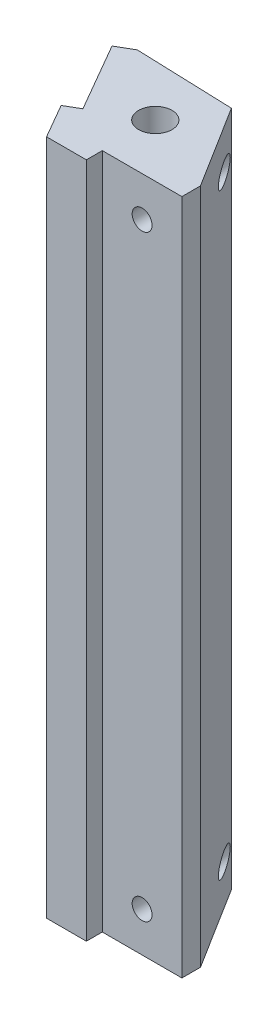
SolidWorks part; units mm, degrees
material "6061-T6 (SS)"
ref_plane "Front Plane" through (0, 0, 0) normal (0, 0, 1) x (1, 0, 0)
ref_plane "Top Plane" through (0, 0, 0) normal (0, 1, 0) x (1, 0, 0)
ref_plane "Right Plane" through (0, 0, 0) normal (1, 0, 0) x (0, 0, -1)
sketch "Sketch1" plane through (0, 0, 0) normal (0, 1, 0) x (1, 0, 0)
  line L0 (0, 0) -> (15, 0)
  line L1 (0, 0) -> (-7.5, 12.9904)
  line L2 (15, 0) -> (15, 4.3301)
  line L3 (0, 0) -> (2.5, 4.3301) construction
  line L6 (-3.75, 15.1554) -> (-7.5, 12.9904)
  line L7 (-3.75, 15.1554) -> (8.5, 14.7224)
  line L8 (8.5, 14.7224) -> (15, 4.3301)
  line L9 (2.5, 4.3301) -> (8.5, 14.7224) construction
  line L10 (-3.75, 15.1554) -> (2.5, 4.3301) construction
  line L11 (2.5, 4.3301) -> (15, 4.3301) construction
  dimension "D4" = 12
  dimension "D1" = 5
  dimension "D2" = 15
  dimension "D3" = 240
extrude "Boss-Extrude1" add sketch "Sketch1" along normal blind 85
sketch "Sketch3" plane through (0, 85, 0) normal (0, 1, 0) x (1, 0, 0)
  line L0 (-7.5, 12.9904) -> (-5.7679, 13.9904)
  line L1 (-3.75, 15.1554) -> (-7.5, 12.9904) construction
  line L2 (-5.7679, 13.9904) -> (-0.7679, 5.3301)
  line L3 (-0.7679, 5.3301) -> (-2.5, 4.3301)
  line L4 (-7.5, 12.9904) -> (0, 0) construction
  line L5 (-2.5, 4.3301) -> (-7.5, 12.9904)
  line L6 (15, 0) -> (15, 2)
  line L7 (15, 0) -> (15, 4.3301) construction
  line L8 (15, 2) -> (5, 2)
  line L9 (5, 2) -> (5, 0)
  line L11 (5, 0) -> (15, 0)
  line L12 (0, 0) -> (15, 0) construction
  dimension "D1" = 2
  dimension "D2" = 5
extrude "Cut-Extrude1" cut sketch "Sketch3" against normal through all
sketch "Sketch4" plane through (0, 85, 0) normal (0, 1, 0) x (1, 0, 0)
  line L0 (0, 0) -> (8.5, 14.7224) construction
  point P4 (5, 8.6603)
  dimension "D1" = 10
hole_wizard "M5x0.8 Tapped Hole1" positions "Sketch6" profile "Sketch7" tap size "M5x0.8" standard "ANSI Metric"
sketch "Sketch6" plane through (0, 85, 0) normal (0, 1, 0) x (1, 0, 0)
  point P0 (5, 8.6603)
sketch "Sketch7" plane through (5, 85, -8.6603) normal (1, 0, 0) x (0, 0, 1)
  line L0 (0, 0) -> (0, 17.2618)
  line L1 (0, 17.2618) -> (2.1, 16)
  line L2 (2.1, 16) -> (2.1, 0)
  line L5 (2.1, 0) -> (0, 0)
  line L10 (0, 17.2618) -> (-2.1, 16) construction
  line L11 (0, -6.35) -> (0, 107.95) construction
  dimension "Tap Drill Dia." = 4.2
  dimension "Tap Drill Depth" = 16
  dimension "Drill Angle" = 118
cosmetic thread "Hole Thread1" parameters "D1"=14, "D2"=5
ref_point "Point1"
hole_wizard "M5x0.8 Tapped Hole2" positions "Sketch11" profile "Sketch10" tap size "M5x0.8" standard "ANSI Metric"
sketch "Sketch11" plane through (0, 0, 0) normal (0, -1, 0) x (-1, 0, 0)
  point P0 (-5, 8.6603)
sketch "Sketch10" plane through (5, 0, -8.6603) normal (1, 0, 0) x (0, 0, -1)
  line L0 (0, 0) -> (0, 17.6618)
  line L1 (0, 17.6618) -> (2.1, 16.4)
  line L2 (2.1, 16.4) -> (2.1, 0)
  line L5 (2.1, 0) -> (0, 0)
  line L10 (0, 17.6618) -> (-2.1, 16.4) construction
  line L11 (0, -6.35) -> (0, 107.95) construction
  dimension "Tap Drill Dia." = 4.2
  dimension "Tap Drill Depth" = 16.4
  dimension "Drill Angle" = 118
cosmetic thread "Hole Thread2" parameters "D1"=14, "D2"=5
sketch "Sketch12" plane through (1.7321, 0, -1) normal (-0.866, 0, 0.5) x (0.5, 0, 0.866)
  line L0 (-15, 42.5) -> (-5, 42.5) construction
  line L1 (-15, 0) -> (-15, 85) construction
  line L2 (-5, 0) -> (-5, 85) construction
  line L3 (-10, 80) -> (-10, 5) construction
  point P8 (-10, 42.5)
  dimension "D1" = 75
hole_wizard "M3x0.5 Tapped Hole1" positions "Sketch14" profile "Sketch13" tap size "M3x0.5" standard "ANSI Metric" end condition through all
sketch "Sketch14" plane through (1.7321, 0, -1) normal (-0.866, 0, 0.5) x (0.5, 0, 0.866)
  point P0 (-10, 80)
  point P3 (-10, 5)
sketch "Sketch13" plane through (-3.2679, 80, -9.6603) normal (0, 1, 0) x (0.5, 0, 0.866)
  line L0 (0, 0) -> (0, 18.5681)
  line L1 (0, 18.5681) -> (1.25, 18.5681)
  line L2 (1.25, 18.5681) -> (1.25, 0)
  line L5 (1.25, 0) -> (0, 0)
  line L11 (0, -6.35) -> (0, 107.95) construction
  dimension "Thru Tap Drill Dia." = 2.5
  dimension "Thru Tap Drill Depth" = 18.5681
cosmetic thread "Hole Thread3" parameters "D2"=3
cosmetic thread "Hole Thread4" parameters "D2"=3
sketch "Sketch15" plane through (0, 0, -2) normal (0, 0, 1) x (1, 0, 0)
  line L0 (5, 42.5) -> (15, 42.5) construction
  line L1 (5, 0) -> (5, 85) construction
  line L2 (15, 0) -> (15, 85) construction
  line L3 (10, 80) -> (10, 5) construction
  point P8 (10, 42.5)
  dimension "D1" = 75
hole_wizard "M3x0.5 Tapped Hole2" positions "Sketch17" profile "Sketch16" tap size "M3x0.5" standard "ANSI Metric" end condition through all
sketch "Sketch17" plane through (0, 0, -2) normal (0, 0, 1) x (1, 0, 0)
  point P0 (10, 80)
  point P3 (10, 5)
sketch "Sketch16" plane through (10, 80, -2) normal (1, 0, 0) x (0, -1, 0)
  line L0 (0, 0) -> (0, 13.1554)
  line L1 (0, 13.1554) -> (1.25, 13.1554)
  line L2 (1.25, 13.1554) -> (1.25, 0)
  line L5 (1.25, 0) -> (0, 0)
  line L11 (0, -6.35) -> (0, 107.95) construction
  dimension "Thru Tap Drill Dia." = 2.5
  dimension "Thru Tap Drill Depth" = 13.1554
cosmetic thread "Hole Thread5" parameters "D2"=3
cosmetic thread "Hole Thread6" parameters "D2"=3
ref_plane "Plane1" through (4.616, 0, -7.9952) normal (-0.5, 0, 0.866) x (0.866, 0, 0.5)
